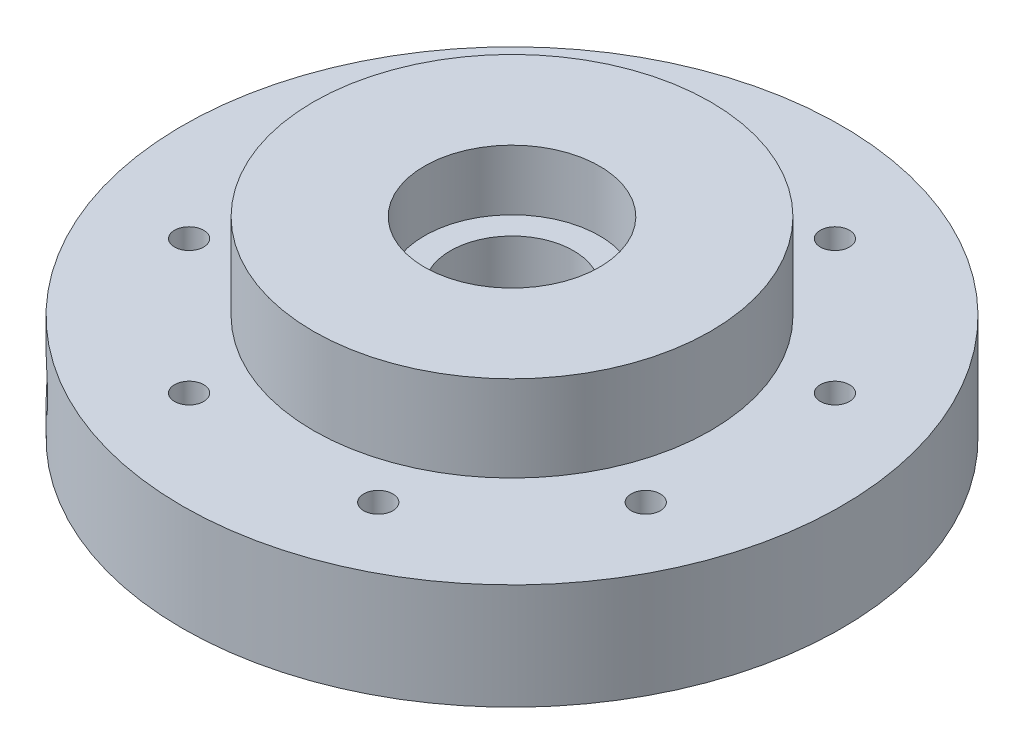
SolidWorks part; units mm, degrees
material "1060 Alloy"
ref_plane "Front" through (0, 0, 0) normal (0, 0, 1) x (1, 0, 0)
ref_plane "Top" through (0, 0, 0) normal (0, 1, 0) x (1, 0, 0)
ref_plane "Right" through (0, 0, 0) normal (1, 0, 0) x (0, 0, -1)
sketch "Sketch1" plane through (0, 0, 0) normal (0, 1, 0) x (1, 0, 0)
  circle A4 centre (0, 0) radius 9.5
  circle A5 centre (0, 0) radius 50.8
  point P0 (0, 0)
  point P17 (0, 0)
  dimension "D6" = 19
  dimension "D1" = 101.6
extrude "body and center hole" add sketch "Sketch1" along normal blind 29.5844
sketch "Sketch5" plane through (0, 29.5844, 0) normal (0, 1, 0) x (1, 0, 0)
  circle A0 centre (0, 0) radius 13.5
  dimension "D1" = 27
extrude "big seal cut" cut sketch "Sketch5" against normal blind 9.3
sketch "Sketch6" plane through (0, 29.5844, 0) normal (0, 1, 0) x (1, 0, 0)
  line L0 (0, 0) -> (0, 50.8) construction
  line L1 (0, 0) -> (19.4403, 46.9331) construction
  circle A0 centre (0, 0) radius 50.8 construction
  circle A1 centre (14.5802, 35.1998) radius 2.25
  dimension "D2" = 4.5
  dimension "D1" = 22.5
  dimension "D3" = 38.1
extrude "impeller housing bolt holes" cut sketch "Sketch6" against normal blind 38
pattern_circular "impeller housing bolt pattern" count 8 over 360 about axis through (0, 0, 0) along (0, 1, 0) of "impeller housing bolt holes"
sketch "Sketch7" plane through (0, 29.5844, 0) normal (0, 1, 0) x (1, 0, 0)
  circle A0 centre (0, 0) radius 30.6267
  circle A1 centre (0, 0) radius 50.8
  circle A3 centre (0, 0) radius 50.8 construction
  dimension "D1" = 61.2534
extrude "impeller recess" cut sketch "Sketch7" against normal blind 13.25
sketch "Sketch8" plane through (0, 0, 0) normal (0, -1, 0) x (-1, 0, 0)
  line L0 (0, 0) -> (0, 50.8) construction
  circle A0 centre (0, 0) radius 25.4 construction
  circle A1 centre (0, -25.4) radius 3
  circle A2 centre (0, 0) radius 50.8 construction
  dimension "D1" = 50.8
  dimension "D2" = 6
extrude "big 4 bolt hole" cut sketch "Sketch8" against normal blind 14.3344 contours A1
pattern_circular "big bolt pattern" count 4 over 360 about axis through (0, 0, 0) along (0, 1, 0) of "big 4 bolt hole"
ref_plane "pressure tap orientation" through (-10.5787, 0, 10.5787) normal (-0.7071, 0, 0.7071) x (0.7071, 0, 0.7071)
sketch "Sketch9" plane through (-10.5787, 0, 10.5787) normal (-0.7071, 0, 0.7071) x (0.7071, 0, 0.7071)
  line L0 (0, 0) -> (0, 16.3344) construction
  line L1 (50.8, 16.3344) -> (-50.8, 16.3344) construction
  circle A0 centre (0, 8.1672) radius 1.5875
  dimension "D1" = 3.175
extrude "vent line" cut sketch "Sketch9" against normal blind 13 and the other way blind 100
sketch "pressure tap plane alignment" plane through (0, 0, 0) normal (0, -1, 0) x (1, 0, 0)
  line L0 (0, 0) -> (-35.921, 35.921) construction
  line L1 (-37.026, 34.7809) -> (-7.7456, 5.5005) construction
  circle A0 centre (0, 0) radius 50.8 construction
ref_plane "pressure tap surface plane" through (-35.921, 0, 35.921) normal (-0.7071, 0, 0.7071) x (0.7071, 0, 0.7071)
sketch "Sketch11" plane through (-35.921, 0, 35.921) normal (-0.7071, 0, 0.7071) x (0.7071, 0, 0.7071)
  circle A0 centre (0, 8.1672) radius 4.1672
  dimension "D1" = 8.3344
extrude "pressure tap" cut sketch "Sketch11" against normal blind 9
equation "\"D6@Sketch1\"=\"impeller boss diameter\"+4mm"
equation "\"D1@body and center hole\"=\"big seal plate thickness\""
equation "\"bearing OD\" = 30mm"
equation "\"bearing outer race thickness\"= 1mm"
equation "\"bearing ID\"= 10mm"
equation "\"bearing depth\"= 9mm"
equation "\"bearing inner race thickness\"= 1mm"
equation "\"small seal OD\" = 20mm"
equation "\"small seal ID\"= 8mm"
equation "\"small seal depth\" = 8.3mm"
equation "\"big seal OD\" = 27mm"
equation "\"big seal ID\"= 15mm"
equation "\"big seal depth\"= 8.3mm"
equation "\"z\" = 8 \t\t\t\t'number of blades"
equation "\"de\" = 0.426in \t\t\t\t'entrance eye diameter"
equation "\"d2\" = 2.097in \t\t\t\t'outer diameter of the impeller "
equation "\"d_exit\" = 0.18in \t\t\t'volute throat aka D4"
equation "\"theta\" = 15"
equation "\"b2\" = .071in\t\t\t\t\t\t\t\t'tip height from disc surface at d2"
equation "\"b1\" = \"b2\" + (\"d2\"/2 - \"de\"/2)*sin(\"theta\")\t\t\t\t'tip height from disc surface at inlet eye"
equation "\"s\" = ( 1/\"z\")*(3.14*\"de\" - (3.14*(\"de\"^2) / (4*(\"b1\"))))\t\t'thickness of blades, calculated from area"
equation "\"s_opening\" = (3.14*\"de\" - \"z\"*\"s\")/\"z\"\t\t\t\t\t'ideal gap between blades, calculated from area"
equation "\"area_eye\"=3.14*(\"de\"^2)/4\t\t\t\t\t\t'eye area"
equation "\"single_channel_area\"=\"s_opening\"*\"b1\"\t\t\t\t\t'ideal area between two blades"
equation "\"impeller upper clearance\"= .5mm"
equation "\"impeller horizontal clearance\"= (\"d2\"*1.15 - \"d2\")/2 \t\t\t\t\t'clearance based on D2-D3 ratio for circular volute, ranges 1.15 to 1.2"
equation "\"impeller bottom clearance\"= .5mm"
equation "\"impeller base thickness\"= 2mm"
equation "\"impeller boss depth\" = \"shaft impeller section length\" + 3mm + \"impeller bolt head depth\" - \"impeller base thickness\""
equation "\"impeller boss diameter\" = \"big seal ID\""
equation "\"impeller dowel diameter\" = 2mm"
equation "\"impeller bolt head diameter\" = 7.5mm"
equation "\"impeller bolt head depth\" = 4mm"
equation "\"impeller shaft bore\"= 8mm"
equation "\"impeller shaft bore depth\" = \"impeller boss depth\" + \"impeller base thickness\" - \"impeller bolt head depth\" - 3mm"
equation "\"impeller dowel length\" = 2mm*2 + \"impeller shaft bore\""
equation "\"impeller screw hole bore\" = 4mm"
equation "\"shaft impeller screw hole diameter\" = \"impeller screw hole bore\""
equation "\"shaft impeller section length\" = \"big seal plate thickness\"/2 + \"impeller bottom clearance\" + \"impeller base thickness\" - \"impeller bolt head depth\" - 3mm"
equation "\"shaft impeller screw hole depth\" = \"shaft impeller section length\"-\"impeller dowel diameter\"-2mm"
equation "\"shaft impeller section diameter\" = \"impeller shaft bore\""
equation "\"shaft seal section diameter\"=\"small seal ID\""
equation "\"shaft seal section length\"= \"big seal plate thickness\"/2 + \"small seal bore\" + 2mm"
equation "\"shaft bearing section diameter\" = \"bearing ID\""
equation "\"shaft bearing section length\" = \"bearing bore\""
equation "\"shaft bearing stop diameter\" = \"bearing ID\" + 2mm"
equation "\"shaft bearing stop length\" = 2mm"
equation "\"shaft coupler section diameter\" = 8mm"
equation "\"shaft coupler section length\" = \"shaft bearing stop length\" + \"coupler length\"/2 + 4mm"
equation "\"coupler motor shaft hole ID\"= 8mm"
equation "\"coupler OD\"= 17mm"
equation "\"coupler length\"= 25mm"
equation "\"square plate diameter\" = 3in"
equation "\"square plate bolt pattern diameter\"= 2in"
equation "\"square plate bolt hole ID\" = 8mm"
equation "\"bearing plate bearing stop ID\" = \"bearing OD\" - 4mm"
equation "\"bearing plate bearing stop depth\" = 3mm"
equation "\"bearing plate thickness\" = \"bearing bore\" + \"bearing plate bearing stop depth\""
equation "\"small seal plate lip depth\" = \"shaft bearing stop length\" + 1mm"
equation "\"small seal plate lip ID\" = \"small seal OD\" - 3mm"
equation "\"small seal plate thickness\" = \"small seal plate lip depth\" + \"small seal bore\""
equation "\"big seal plate lip depth\" = 8mm"
equation "\"big seal plate thickness\" = \"big seal plate outer thickness\" + \"big seal plate riser height\""
equation "\"motor to housing distance\" = \"motor shaft pride\" + \"shaft coupler section length\" - \"bearing plate bearing stop depth\" + 2mm"
equation "\"motor mount coupler hole diameter\"= \"coupler OD\"+ 4mm"
equation "\"motor mount to housing post radius\"= ( 3 * \"square plate bolt hole ID\" ) / 2"
equation "\"motor mount m4 screw hole diameter\"= 4mm"
equation "\"motor mount m4 head diameter\"= 7.25mm"
equation "\"motor mount m4 head depth\"= 4mm"
equation "\"motor mount plate thickness\"= 8mm + \"motor mount m4 head depth\""
equation "\"impeller cavity center height\"= \"impeller bottom clearance\" + \"impeller upper clearance\" + \"final impeller center height\""
equation "\"impeller cavity diameter\"= 2 * \"impeller horizontal clearance\" + \"d2\" \t\t\t'called D3 analytically"
equation "\"impeller cavity outer height\"= \"impeller bottom clearance\" + \"impeller upper clearance\" + \"impeller base thickness\" + \"b2\" \t\t\t'this is height at impeller diameter d2, not at d3"
equation "\"motor shaft pride\"= 32mm"
equation "\"motor shaft flat section length from tip\"= 25.7mm"
equation "\"motor shaft bore end clearance\"= 2mm"
equation "\"coupler shaft to motor clearance\" = 2mm"
equation "\"motor mount shaft hole depth\"= \"motor shaft pride\""
equation "\"impeller housing bolt count\" = 8"
equation "\"impeller housing bolt diameter\" = 6mm"
equation "\"impeller housing bolt pattern diameter\" = 3in"
equation "\"impeller housing o-ring channel height\"= 1.5mm"
equation "\"impeller housing o ring channel width\"= 1.5mm"
equation "\"impeller housing o-ring diameter\" = 2in"
equation "\"impeller housing threaded inlet diameter\" = 0.6875in \t\t\t'this is the 11/16 drill size for 1/2 npt fitting"
equation "\"impeller housing threaded inlet depth\"= 20mm"
equation "\"impeller housing thickness\"= \"impeller housing exit threaded diameter\" + 2*\"impeller housing outlet purchase\""
equation "\"impeller housing exit threaded diameter\"= 0.6875in \t\t\t'this is the 11/16 drill size for 1/2 npt fitting"
equation "\"impeller housing exit threaded depth\"= 12mm"
equation "\"impeller housing diameter\" = 4in"
equation "\"impeller housing diffuser conical angle\"=10"
equation "\"impeller housing diffuser tangent angle\"=0"
equation "\"impeller housing outlet purchase\" = 6mm"
equation "\"D1@Sketch1\"=\"impeller housing diameter\""
equation "\"D1@Sketch5\"=\"big seal OD\""
equation "\"D1@big seal cut\"=\"big seal bore\""
equation "\"D1@Sketch6\"=360 / \"impeller housing bolt count\" / 2"
equation "\"D2@Sketch6\"=\"impeller housing bolt diameter\"-1.5mm"
equation "\"D3@Sketch6\"=\"impeller housing bolt pattern diameter\"/2"
equation "\"D1@Sketch7\"=\"impeller cavity diameter\""
equation "\"D1@impeller recess\"=\"big seal plate riser height\""
equation "\"D1@Sketch8\"=\"square plate bolt pattern diameter\""
equation "\"D2@Sketch8\"=\"square plate bolt hole ID\"-2mm"
equation "\"D1@big 4 bolt hole\"=\"big seal plate outer thickness\"-2mm"
equation "\"inlet area before cut\" = \"minimum channel width\" * (\"z\") * \"b1\"\t\t\t\t'if minimum channel width>s_opening, this is larger than area_eye"
equation "\"area to cut\" = \"inlet area before cut\" - \"area_eye\"\t\t\t\t\t\t'amount of extra area\t\t\t\t\t"
equation "\"height to cut\" = \"area to cut\" / ((\"z\")* \"minimum channel width\")+ .0001in\t\t\t'the 0.0001 in cut is to avoid errors in model"
equation "\"final impeller center height\" = \"impeller base thickness\" + \"b1\" - \"height to cut\"\t\t'corrected height so that sum of channel areas equals eye area"
equation "\"big seal plate pressure hole diameter\" = .125in\t\t\t'this is 1/8 drill "
equation "\"big seal plate pressure tap diameter\" = .328125in \t\t'this is 21/64 drill for a 1/8 ANPT tap"
equation "\"big seal plate pressure tap depth\" = 9mm"
equation "\"motor mount m4 pattern diamater\" = 30mm"
equation "\"bearing bore\" = \"bearing depth\" + 1mm"
equation "\"small seal bore\" = \"small seal depth\" + 1mm"
equation "\"big seal bore\" = \"big seal depth\" + 1mm"
equation "\"D1@impeller housing bolt pattern\"=\"impeller housing bolt count\""
equation "\"big seal plate outer thickness\" = \"big seal plate pressure tap diameter\" + (\"impeller housing outlet purchase\"-2mm)*2"
equation "\"impeller housing diffuser length\" = 1.5in"
equation "\"minimum channel width\" = \"s_opening\"\t\t\t\t\t\t\t\t'minimum s, set this to a bit size for milling or to s_opening for DMLS"
equation "\"big seal plate riser height\" = 13.25mm\t\t'this is a reference dimension that needs to be taken from the impeller housing drawing"
equation "\"D1@Sketch9\"=\"big seal plate pressure hole diameter\""
equation "\"D1@Sketch11\"=\"big seal plate pressure tap diameter\""
equation "\"D1@pressure tap\" = \"big seal plate pressure tap depth\""
